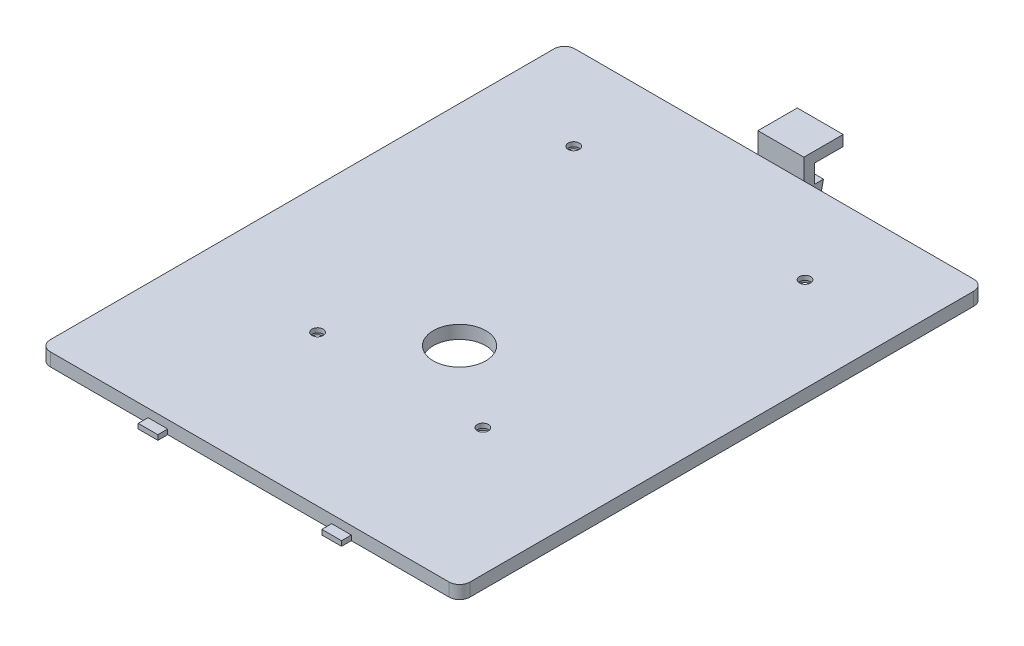
SolidWorks part; units mm, degrees
ref_plane "Front Plane" through (0, 0, 0) normal (0, 0, 1) x (1, 0, 0)
ref_plane "Top Plane" through (0, 0, 0) normal (0, 1, 0) x (1, 0, 0)
ref_plane "Right Plane" through (0, 0, 0) normal (1, 0, 0) x (0, 0, -1)
sketch "Sketch1" plane through (0, 0, 0) normal (0, 1, 0) x (1, 0, 0)
  line L1 (50.8, 0) -> (-50.8, 0)
  line L2 (50.8, 0) -> (50.8, 127)
  line L3 (50.8, 127) -> (-50.8, 127)
  line L4 (-50.8, 0) -> (-50.8, 127)
  point P11 (0, 0)
  dimension "D1" = 127
  dimension "D2" = 101.6
extrude "Boss-Extrude1" add sketch "Sketch1" along normal blind 3.175
sketch "Sketch2" plane through (0, 0, 0) normal (0, -1, 0) x (1, 0, 0)
  line L0 (-50.8, 0) -> (50.8, 0) construction
  line L1 (-24.6062, 0) -> (-19.8438, 0)
  line L2 (-24.6062, 0) -> (-24.6062, 2.3813)
  line L3 (-24.6062, 2.3813) -> (-19.8438, 2.3813)
  line L4 (-19.8438, 0) -> (-19.8438, 2.3813)
  line L12 (0, -55) -> (0, 55) construction
  line L13 (24.6062, 2.3813) -> (19.8438, 2.3813)
  line L14 (24.6062, 0) -> (24.6062, 2.3813)
  line L15 (24.6062, 0) -> (19.8438, 0)
  line L16 (19.8438, 0) -> (19.8438, 2.3813)
  dimension "D1" = 2.3813
  dimension "D2" = 4.7625
  dimension "D3" = 19.8438
extrude "Boss-Extrude2" add sketch "Sketch2" against normal blind 1.1906
fillet "Fillet1" radius 2.54 4 edges at (-50.8, 1.5875, 0) (50.8, 1.5875, 0) (-50.8, 1.5875, -127) (50.8, 1.5875, -127)
sketch "Sketch4" plane through (0, 0, 0) normal (1, 0, 0) x (0, 0, -1)
  line L0 (120.65, 0) -> (126.1111, -5.4611)
  line L1 (2.54, 0) -> (124.46, 0) construction
  line L2 (129.8509, -4.3774) -> (130.175, -2.9369)
  line L3 (130.175, -2.9369) -> (128.5875, -2.9369)
  line L4 (128.5875, -2.9369) -> (128.5875, 6.5881)
  line L5 (128.5875, 6.5881) -> (138.1125, 6.5881)
  line L6 (138.1125, 6.5881) -> (138.1125, 4.0481)
  line L7 (138.1125, 4.0481) -> (131.1275, 4.0481)
  line L8 (131.1275, 4.0481) -> (131.1275, -0.3969)
  line L9 (131.1275, -0.3969) -> (133.35, -0.3969)
  line L10 (133.35, -0.3969) -> (132.3289, -4.9349)
  line L11 (124.315, -7.2571) -> (117.0579, 0)
  line L12 (127, 3.175) -> (127, 0) construction
  line L13 (124.46, 0) -> (127, 0) construction
  line L14 (117.0579, 0) -> (120.65, 0)
  arc A0 (126.1111, -5.4611) -> (129.8509, -4.3774) centre (127.6826, -3.8895) ccw
  arc A1 (132.3289, -4.9349) -> (124.315, -7.2571) centre (127.6826, -3.8895) cw
  point P20 (128.3012, -6.0242)
  point P21 (129.0081, -8.4638)
  dimension "D4" = 2.54
  dimension "D14" = 4.7625
  dimension "D1" = 45
  dimension "D2" = 6.35
  dimension "D3" = 2.54
  dimension "D5" = 2.54
  dimension "D6" = 2.54
  dimension "D7" = 2.54
  dimension "D8" = 2.54
  dimension "D9" = 0.3969
  dimension "D10" = 9.525
  dimension "D11" = 9.525
  dimension "D12" = 1.5875
  dimension "D13" = 3.175
  dimension "D15" = 6.35
extrude "Boss-Extrude3" add sketch "Sketch4" along normal mid plane 11.1125
hole_wizard "CBORE for M2.5 Hex Head Machine Screw1" positions "Sketch7" profile "Sketch6" counterbore size "M2.5" standard "ANSI Metric" end condition through all
sketch "Sketch7" plane through (0, 0, 0) normal (0, -1, 0) x (-1, 0, 0)
  line L0 (0, 55) -> (0, -55) construction
  line L1 (50.8, 124.46) -> (50.8, 2.54) construction
  line L3 (-48.26, 127) -> (48.26, 127) construction
  line L4 (48.26, 0) -> (-48.26, 0) construction
  point P0 (20, 36.4358)
  point P3 (28, 106.4358)
  point P9 (-20, 36.4358)
  point P10 (-28, 106.4358)
  point P17 (0, 0)
  point P18 (20, 36.3132)
  point P19 (20, 36.4358)
  dimension "D1" = 30.8
  dimension "D2" = 36.4358
  dimension "D3" = 22.8
  dimension "D4" = 20.5642
sketch "Sketch6" plane through (-20, 0, -36.4358) normal (1, 0, 0) x (0, 0, -1)
  line L0 (0, 0) -> (0, 6.5881)
  line L1 (0, 6.5881) -> (1.35, 6.5881)
  line L3 (1.35, 6.5881) -> (1.35, 2.1)
  line L4 (1.35, 2.1) -> (3.64, 2.1)
  line L5 (3.64, 2.1) -> (3.64, 0)
  line L7 (3.64, 0) -> (0, 0)
  line L11 (0, -6.35) -> (0, 107.95) construction
  dimension "Thru Hole Dia." = 2.7
  dimension "Thru Hole Depth" = 6.5881
  dimension "C'Bore Dia." = 7.28
  dimension "C'Bore Depth" = 2.1
sketch "Sketch8" plane through (0, 3.175, 0) normal (0, 1, 0) x (1, 0, 0)
  line L0 (-48.26, 0) -> (48.26, 0) construction
  line L1 (-50.8, 124.46) -> (-50.8, 2.54) construction
  circle A0 centre (0, 50.8) radius 6.35
  dimension "D1" = 12.7
  dimension "D3" = 50.8
  dimension "D2" = 50.8
extrude "Cut-Extrude1" cut sketch "Sketch8" against normal through all
